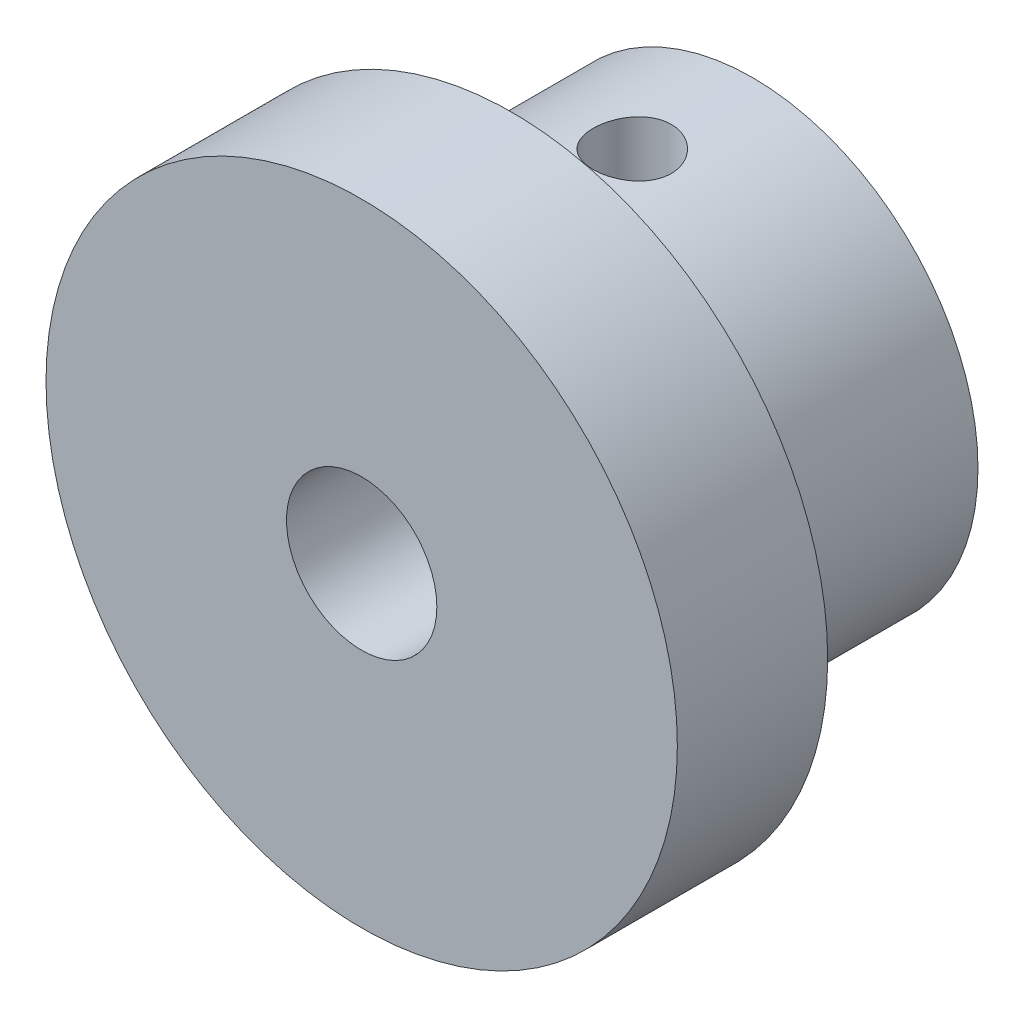
SolidWorks part; units mm, degrees
ref_plane "Front Plane" through (0, 0, 0) normal (0, 0, 1) x (1, 0, 0)
ref_plane "Top Plane" through (0, 0, 0) normal (0, 1, 0) x (1, 0, 0)
ref_plane "Right Plane" through (0, 0, 0) normal (1, 0, 0) x (0, 0, -1)
sketch "Sketch1" plane through (0, 0, 0) normal (0, 0, 1) x (1, 0, 0)
  circle A0 centre (0, 0) radius 7.5
extrude "Boss-Extrude1" add sketch "Sketch1" along normal blind 8
sketch "Sketch2" plane through (0, 0, 8) normal (0, 0, 1) x (1, 0, 0)
  circle A0 centre (0, 0) radius 10.5
extrude "Boss-Extrude2" add sketch "Sketch2" along normal blind 5
sketch "Sketch3" plane through (0, 0, 13) normal (0, 0, 1) x (1, 0, 0)
  circle A0 centre (0, 0) radius 2.5
extrude "Cut-Extrude1" cut sketch "Sketch3" against normal through all
hole_wizard "Tap Drill for M3x0.5 Tap1" positions "3DSketch1" profile "Sketch4" hole size "M3x0.5" standard "JIS"
sketch3d "3DSketch1"
  point P0 (0, 7.5, 4)
  point P3 (0, 0, 0)
sketch "Sketch4" plane through (0, 7.5, 4) normal (1, 0, 0) x (0, 0, 1)
  line L0 (0, 0) -> (0, 5)
  line L1 (0, 5) -> (1.3, 5)
  line L2 (1.3, 5) -> (1.3, 0)
  line L5 (1.3, 0) -> (0, 0)
  line L11 (0, -6.35) -> (0, 107.95) construction
  dimension "Thru Hole Dia." = 2.6
  dimension "Thru Hole Depth" = 5
